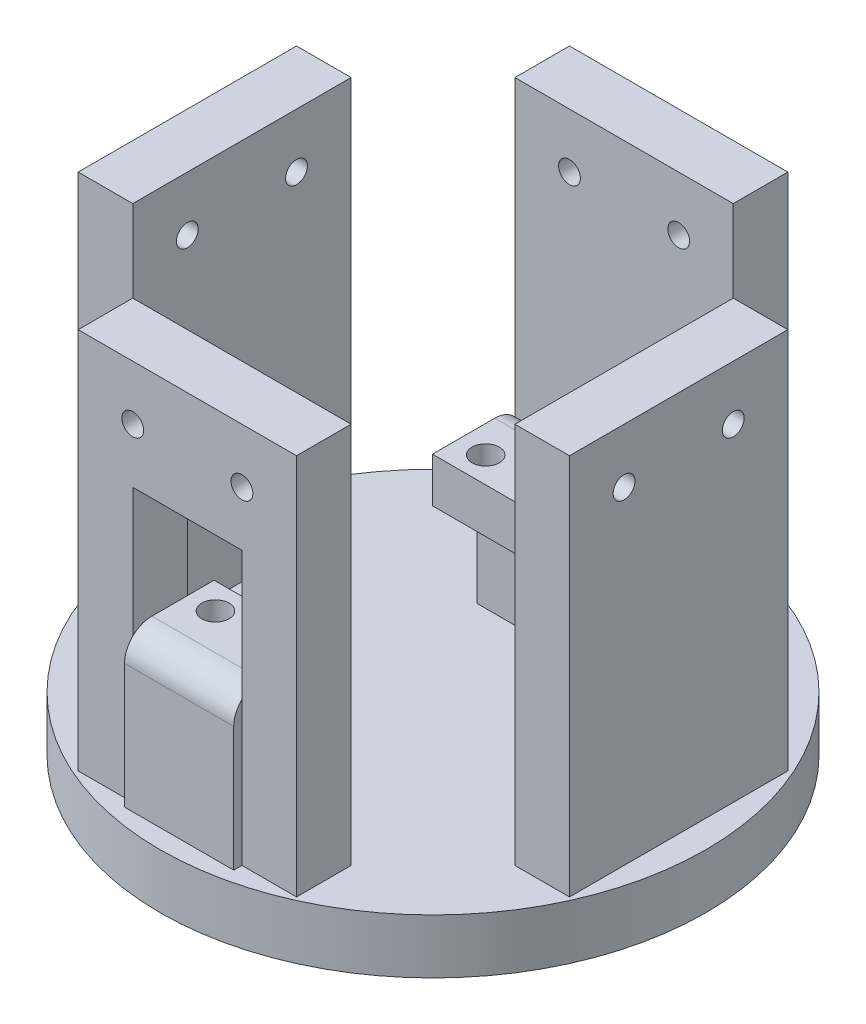
SolidWorks part; units mm, degrees
ref_plane "Front Plane" through (0, 0, 0) normal (0, 0, 1) x (1, 0, 0)
ref_plane "Top Plane" through (0, 0, 0) normal (0, 1, 0) x (1, 0, 0)
ref_plane "Right Plane" through (0, 0, 0) normal (1, 0, 0) x (0, 0, -1)
sketch "Sketch1" plane through (0, 0, 0) normal (0, 1, 0) x (1, 0, 0)
  circle A0 centre (0, 0) radius 50
  dimension "D1" = 100
extrude "Boss-Extrude1" add sketch "Sketch1" along normal blind 10
sketch "Sketch2" plane through (0, 10, 0) normal (0, 1, 0) x (1, 0, 0)
  line L0 (0, 0) -> (0, 9.9)
  line L1 (0, 0) -> (0, -30.1)
  line L2 (0, -30.1) -> (10, -30.1)
  line L3 (10, -30.1) -> (10, 9.9)
  line L4 (10, 9.9) -> (-10, 9.9)
  line L6 (-10, -30.1) -> (0, -30.1)
  line L7 (10, 9.9) -> (10, 17.15)
  line L8 (10, -30.1) -> (10, -37.35)
  line L9 (10, 17.15) -> (-10, 17.15)
  line L10 (-10, 17.15) -> (-10, -37.35)
  line L11 (-10, -37.35) -> (10, -37.35)
  line L12 (10, -30.1) -> (10, -38.3)
  line L13 (10, -38.3) -> (-10, -38.3)
  line L14 (-10, -38.3) -> (-10, -30.1)
  line L15 (10, -38.3) -> (10, -46.5)
  line L16 (10, -46.5) -> (-10, -46.5)
  line L17 (-10, -46.5) -> (-10, -38.3)
  line L18 (10, 9.9) -> (10, 18.1)
  line L19 (10, 18.1) -> (10, 26.3)
  line L20 (10, 26.3) -> (-10, 26.3)
  line L21 (-10, 26.3) -> (-10, 18.1)
  line L22 (-10, 18.1) -> (10, 18.1)
  circle A0 centre (0, 0) radius 2.5
  dimension "D1" = 9.9
  dimension "D2" = 30.1
  dimension "D3" = 10
  dimension "D4" = 20
  dimension "D5" = 7.25
  dimension "D6" = 7.25
  dimension "D7" = 8.2
  dimension "D8" = 8.2
  dimension "D9" = 8.2
  dimension "D10" = 8.2
extrude "Boss-Extrude2" add sketch "Sketch2" along normal blind 27.8 contours L17 L16 L15 L13 | L21 L22 L19 L20
sketch "Sketch3" plane through (0, 0, 38.3) normal (0, 0, -1) x (-1, 0, 0)
  line L0 (-10, 37.8) -> (-10, 29.6)
  line L1 (-10, 37.8) -> (-10, 10) construction
  line L2 (-10, 29.6) -> (10, 29.6)
  line L3 (10, 37.8) -> (10, 10) construction
  line L4 (10, 29.6) -> (10, 37.8)
  line L5 (10, 37.8) -> (-10, 37.8)
  dimension "D1" = 8.2
extrude "Boss-Extrude3" add sketch "Sketch3" along normal blind 8.2
sketch "Sketch4" plane through (0, 0, -18.1) normal (0, 0, 1) x (1, 0, 0)
  line L0 (10, 37.8) -> (10, 29.6008)
  line L1 (10, 37.8) -> (10, 10) construction
  line L2 (10, 29.6008) -> (-10, 29.6008)
  line L3 (-10, 37.8) -> (-10, 10) construction
  line L4 (-10, 29.6008) -> (-10, 37.8)
  line L5 (-10, 37.8) -> (10, 37.8)
extrude "Boss-Extrude4" add sketch "Sketch4" along normal blind 8.2
sketch "Sketch5" plane through (0, 10, 0) normal (0, 1, 0) x (1, 0, 0)
  line L4 (-10, -35) -> (-10, -45)
  line L5 (0, 0) -> (-35, 0)
  line L19 (-35, 0) -> (-35, 20)
  line L20 (-35, 20) -> (-45, 20)
  line L21 (-45, 20) -> (-45, -20)
  line L22 (-45, -20) -> (-35, -20)
  line L23 (-35, -20) -> (-35, 0)
  line L24 (35, -20) -> (35, 0)
  line L25 (45, -20) -> (35, -20)
  line L26 (45, 20) -> (45, -20)
  line L27 (35, 20) -> (45, 20)
  line L28 (35, 0) -> (35, 20)
  line L29 (-20, 35) -> (-20, 45)
  line L30 (-20, 45) -> (20, 45)
  line L31 (20, 45) -> (20, 35)
  line L32 (20, 35) -> (0, 35)
  line L33 (0, 35) -> (-20, 35)
  line L36 (20, -45) -> (20, -35)
  line L38 (-20, -35) -> (-20, -45)
  line L39 (-10, -46.5) -> (-10, -38.3) construction
  line L40 (10, -35) -> (10, -45)
  line L41 (10, -38.3) -> (10, -46.5) construction
  line L42 (-10, -35) -> (-20, -35)
  line L43 (-10, -45) -> (-20, -45)
  line L44 (20, -45) -> (10, -45)
  line L45 (20, -35) -> (10, -35)
  dimension "D2" = 35
  dimension "D4" = 10
  dimension "D5" = 20
  dimension "D6" = 40
fillet "Fillet1" radius 5 2 edges at (0, 37.8, 46.5) (0, 37.8, -26.3)
sketch "Sketch7" plane through (0, 37.8, 0) normal (0, 1, 0) x (1, 0, 0)
  line L0 (0, -41.5) -> (0, 21.3)
  line L1 (-10, -41.5) -> (10, -41.5) construction
  line L2 (10, 21.3) -> (-10, 21.3) construction
  line L3 (0, -10.1) -> (5, -10.1)
  line L4 (5, -10.1) -> (5, -34.85)
  line L5 (5, -34.85) -> (-5, -34.85)
  line L6 (-5, -34.85) -> (-5, 14.65)
  line L7 (-5, 14.65) -> (5, 14.65)
  line L8 (5, 14.65) -> (5, -10.1)
  circle A0 centre (5, 14.65) radius 2.5
  circle A1 centre (-5, 14.65) radius 2.5
  circle A2 centre (-5, -34.85) radius 2.5
  circle A3 centre (5, -34.85) radius 2.5
  dimension "D1" = 5
  dimension "D2" = 24.75
  dimension "D3" = 10
  dimension "D4" = 49.5
  dimension "D5" = 24.75
extrude "Cut-Extrude1" cut sketch "Sketch7" against normal blind 9 contours A0 | A1 | A3 | A2
extrude "Boss-Extrude5" add sketch "Sketch5" along normal blind 70 contours L28 L24 L25 L26 L27 | L22 L23 L19 L20 L21 | L43 L38 L42 L4 | L45 L40 L44 L36 | L29 L30 L31 L32 L33
sketch "Sketch8" plane through (10, 0, 0) normal (-1, 0, 0) x (0, 0, 1)
  line L0 (45, 80) -> (45, 60)
  line L1 (45, 80) -> (45, 36.3707) construction
  line L2 (45, 60) -> (35, 60)
  line L3 (35, 80) -> (35, 37.8) construction
  line L4 (35, 60) -> (35, 80)
  line L5 (35, 80) -> (45, 80) construction
  line L6 (35, 80) -> (45, 80)
  dimension "D1" = 20
extrude "Boss-Extrude6" add sketch "Sketch8" along normal up to next
hole_wizard "Ø4.0 (4) Diameter Hole1" positions "Sketch9" profile "Sketch10" hole size "Ø4.0" standard "ISO" end condition through all
sketch "Sketch9" plane through (0, 0, 45) normal (0, 0, 1) x (1, 0, 0)
  line L0 (0, 80) -> (0, 70)
  line L1 (20, 80) -> (-20, 80) construction
  line L2 (0, 70) -> (0, 60)
  line L3 (-10, 60) -> (10, 60) construction
  line L5 (20, 70) -> (10, 70)
  line L6 (20, 80) -> (20, 10) construction
  line L7 (10, 70) -> (-10, 70)
  line L8 (-10, 70) -> (-20, 70)
  line L9 (-20, 80) -> (-20, 10) construction
  point P13 (10, 70)
  point P17 (-10, 70)
  dimension "D1" = 10
  dimension "D2" = 10
  dimension "D3" = 10
  dimension "D4" = 20
  dimension "D5" = 10
sketch "Sketch10" plane through (-10, 70, 45) normal (1, 0, 0) x (0, -1, 0)
  line L0 (0, 0) -> (0, 95)
  line L1 (0, 95) -> (2, 95)
  line L2 (2, 95) -> (2, 0)
  line L5 (2, 0) -> (0, 0)
  line L11 (0, -6.35) -> (0, 107.95) construction
  dimension "Thru Hole Dia." = 4
  dimension "Thru Hole Depth" = 95
hole_wizard "Ø4.0 (4) Diameter Hole2" positions "Sketch11" profile "Sketch12" hole size "Ø4.0" standard "ISO" end condition through all
sketch "Sketch11" plane through (45, 0, 0) normal (1, 0, 0) x (0, 0, -1)
  line L0 (20, 80) -> (20, 70)
  line L1 (20, 80) -> (20, 10) construction
  line L2 (20, 70) -> (10, 70)
  line L3 (10, 70) -> (-10, 70)
  line L5 (-20, 80) -> (-20, 10) construction
  point P7 (10, 70)
  point P9 (-10, 70)
  dimension "D1" = 10
  dimension "D2" = 10
  dimension "D3" = 20
  dimension "D4" = 10
sketch "Sketch12" plane through (45, 70, 10) normal (0, 1, 0) x (0, 0, -1)
  line L0 (0, 0) -> (0, 95)
  line L1 (0, 95) -> (2, 95)
  line L2 (2, 95) -> (2, 0)
  line L5 (2, 0) -> (0, 0)
  line L11 (0, -6.35) -> (0, 107.95) construction
  dimension "Thru Hole Dia." = 4
  dimension "Thru Hole Depth" = 95
hole_wizard "Ø4.0 (4) Diameter Hole3" positions "Sketch13" profile "Sketch14" hole size "Ø4.0" standard "ISO" end condition up to next
sketch "Sketch13" plane through (0, 10, 0) normal (0, 1, 0) x (1, 0, 0)
  line L0 (0, 0) -> (20, 0)
  line L2 (0, 0) -> (-20, 0)
  point P2 (20, 0)
  point P6 (-20, 0)
  dimension "D1" = 20
  dimension "D2" = 20
sketch "Sketch14" plane through (-20, 10, 0) normal (1, 0, 0) x (0, 0, 1)
  line L0 (0, 0) -> (0, 10)
  line L1 (0, 10) -> (2, 10)
  line L2 (2, 10) -> (2, 0)
  line L5 (2, 0) -> (0, 0)
  line L11 (0, -6.35) -> (0, 107.95) construction
  dimension "Thru Hole Dia." = 4
  dimension "Thru Hole Depth" = 10
